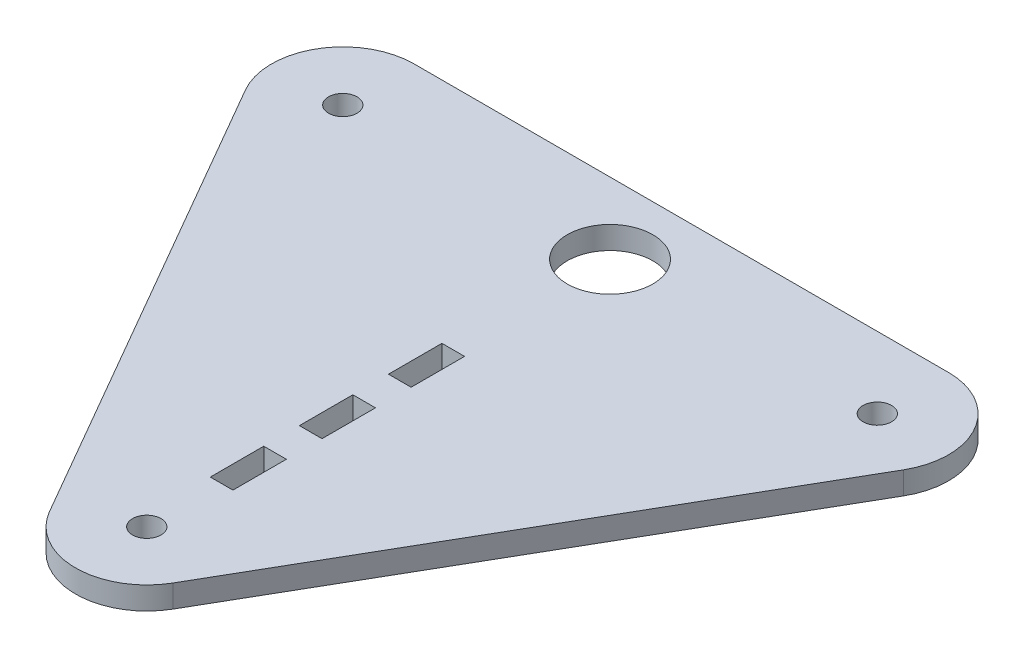
SolidWorks part; units mm, degrees
ref_plane "Plan de face" through (0, 0, 0) normal (0, 0, 1) x (1, 0, 0)
ref_plane "Plan de dessus" through (0, 0, 0) normal (0, 1, 0) x (1, 0, 0)
ref_plane "Plan de droite" through (0, 0, 0) normal (1, 0, 0) x (0, 0, -1)
sketch "Esquisse1" plane through (0, 0, 0) normal (0, 1, 0) x (1, 0, 0)
  line L0 (-92.3237, 55.0056) -> (-17.3237, -74.9944)
  line L1 (92.3237, 55.0056) -> (17.3237, -74.9944)
  line L2 (-75, 85) -> (75, 85)
  circle A0 centre (-75, 65) radius 4
  circle A1 centre (75, 65) radius 4
  circle A2 centre (0, -65) radius 4
  arc A3 (-75, 85) -> (-92.3237, 55.0056) centre (-75, 65) ccw
  arc A4 (92.3237, 55.0056) -> (75, 85) centre (75, 65) ccw
  arc A5 (-17.3237, -74.9944) -> (17.3237, -74.9944) centre (0, -65) ccw
  dimension "D1" = 8
  dimension "D6" = 40
  dimension "D2" = 65
  dimension "D3" = 65
  dimension "D4" = 150
  dimension "D5" = 75
extrude "Boss.-Extru.1" add sketch "Esquisse1" along normal blind 6.35 contours L1 A5 L0 A3 L2 A4 | A2 | A1 | A0
sketch "Esquisse2" plane through (0, 6.35, 0) normal (0, 1, 0) x (1, 0, 0)
  line L1 (-3.175, -4) -> (3.175, -4)
  line L2 (-3.175, -4) -> (-3.175, -19)
  line L3 (-3.175, -19) -> (3.175, -19)
  line L4 (3.175, -4) -> (3.175, -19)
  line L5 (-3.175, -4) -> (3.175, -19) construction
  line L6 (-3.175, -19) -> (3.175, -4) construction
  line L7 (3.175, 21) -> (-3.175, 21)
  line L8 (-3.175, -29) -> (3.175, -29)
  line L9 (-3.175, -29) -> (-3.175, -44)
  line L10 (-3.175, -44) -> (3.175, -44)
  line L11 (3.175, -29) -> (3.175, -44)
  line L12 (-3.175, -29) -> (3.175, -44) construction
  line L13 (-3.175, -44) -> (3.175, -29) construction
  line L14 (3.175, 21) -> (3.175, 6)
  line L15 (3.175, 6) -> (-3.175, 6)
  line L16 (-3.175, 21) -> (-3.175, 6)
  line L17 (3.175, 21) -> (-3.175, 6) construction
  line L18 (3.175, 6) -> (-3.175, 21) construction
  point P0 (0, -11.5)
  point P5 (0, 13.5)
  point P9 (0, -36.5)
  point P14 (0, -29)
  point P17 (0, 6)
  dimension "D1" = 6.35
  dimension "D2" = 15
  dimension "D3" = 4
  dimension "D4" = 10
  dimension "D5" = 15
  dimension "D6" = 10
extrude "Enlèv. mat.-Extru.1" cut sketch "Esquisse2" against normal through all
sketch "Esquisse3" plane through (0, 6.35, 0) normal (0, 1, 0) x (1, 0, 0)
  line L0 (-75, 65) -> (75, 65) construction
  circle A0 centre (0, 65) radius 12
  dimension "D1" = 24
extrude "Enlèv. mat.-Extru.2" cut sketch "Esquisse3" against normal through all
